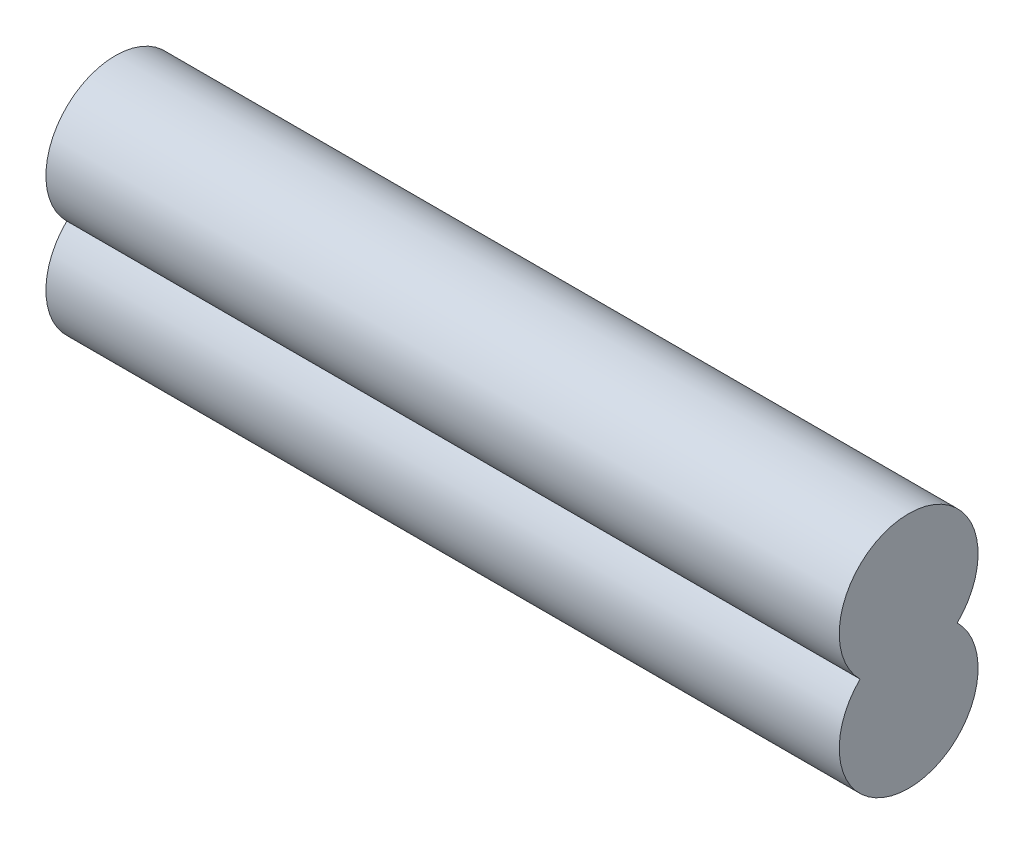
SolidWorks part; units mm, degrees
ref_plane "Front Plane" through (0, 0, 0) normal (0, 0, 1) x (1, 0, 0)
ref_plane "Top Plane" through (0, 0, 0) normal (0, 1, 0) x (1, 0, 0)
ref_plane "Right Plane" through (0, 0, 0) normal (1, 0, 0) x (0, 0, -1)
sketch "Sketch2" plane through (0, 0, 0) normal (1, 0, 0) x (0, 0, -1)
  line L1 (6.35, 6.35) -> (-6.35, 6.35)
  line L2 (6.35, 6.35) -> (6.35, -6.35)
  line L3 (6.35, -6.35) -> (-6.35, -6.35)
  line L4 (-6.35, 6.35) -> (-6.35, -6.35)
  line L5 (6.35, 6.35) -> (-6.35, -6.35) construction
  line L6 (6.35, -6.35) -> (-6.35, 6.35) construction
  point P0 (0, 0)
  dimension "D1" = 12.7
  dimension "D2" = 12.7
extrude "Boss-Extrude1" add sketch "Sketch2" along normal blind 40.64
sketch "Sketch3" plane through (0, 0, 0) normal (-1, 0, 0) x (0, 0, 1)
  line L0 (0, -6.35) -> (0, 6.35) construction
  line L1 (6.35, -6.35) -> (-6.35, -6.35) construction
  line L2 (-6.35, 6.35) -> (6.35, 6.35) construction
  line L3 (6.35, 0) -> (-6.35, 0) construction
  line L4 (6.35, 6.35) -> (6.35, -6.35) construction
  line L5 (-6.35, -6.35) -> (-6.35, 6.35) construction
  line L7 (6.35, -6.35) -> (-6.35, -6.35)
  line L8 (6.35, -6.35) -> (6.35, 6.35)
  line L9 (6.35, 6.35) -> (-6.35, 6.35)
  line L10 (-6.35, -6.35) -> (-6.35, 6.35)
  line L11 (6.35, -6.35) -> (-6.35, 6.35) construction
  line L12 (6.35, 6.35) -> (-6.35, -6.35) construction
  circle A0 centre (0, -2.54) radius 3.556
  circle A1 centre (0, 2.54) radius 3.556
  point P16 (0, 0)
  line M3 (6.35, -6.35) -> (6.35, 6.35)
  line M4 (6.35, 6.35) -> (-6.35, 6.35)
  line M5 (-6.35, 6.35) -> (-6.35, -6.35)
  line M6 (-6.35, -6.35) -> (6.35, -6.35)
  dimension "D1" = 7.112
  dimension "D2" = 7.112
  dimension "D3" = 2.54
  dimension "D4" = 2.54
extrude "Cut-Extrude2" cut sketch "Sketch3" against normal through all contours A1 A0 M6 M3 M4 M5
